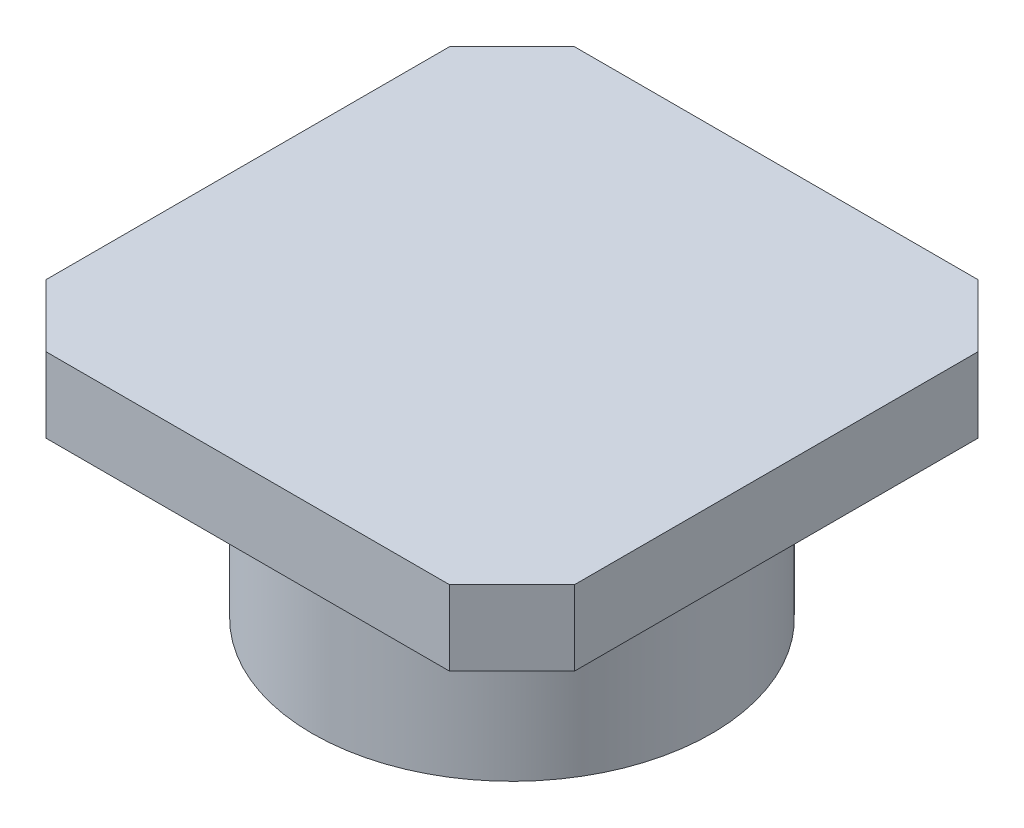
SolidWorks part; units mm, degrees
ref_plane "Front Plane" through (0, 0, 0) normal (0, 0, 1) x (1, 0, 0)
ref_plane "Top Plane" through (0, 0, 0) normal (0, 1, 0) x (1, 0, 0)
ref_plane "Right Plane" through (0, 0, 0) normal (1, 0, 0) x (0, 0, -1)
sketch "Sketch1" plane through (0, 0, 0) normal (0, 1, 0) x (1, 0, 0)
  circle A0 centre (0, 0) radius 12.5
  circle A1 centre (0, 0) radius 16
extrude "Extrude1" add sketch "Sketch1" along normal blind 15
sketch "Sketch2" plane through (0, 15, 0) normal (0, 1, 0) x (1, 0, 0)
  circle A0 centre (0, 0) radius 30
extrude "Extrude2" add sketch "Sketch2" along normal blind 6
fillet "Fillet1" radius 2 1 edges at (0, 15, 16)
sketch "Sketch5" plane through (0, 21, 0) normal (0, 1, 0) x (1, 0, 0)
  line L0 (-21.1693, 16.1693) -> (-16.1693, 21.1693)
  line L1 (-34.3735, 34.3735) -> (34.3735, 34.3735)
  line L2 (-34.3735, 34.3735) -> (-34.3735, -34.3735)
  line L3 (-34.3735, -34.3735) -> (34.3735, -34.3735)
  line L4 (34.3735, 34.3735) -> (34.3735, -34.3735)
  line L5 (-34.3735, 34.3735) -> (34.3735, -34.3735) construction
  line L6 (-34.3735, -34.3735) -> (34.3735, 34.3735) construction
  line L7 (-16.1693, -21.1693) -> (16.1693, -21.1693)
  line L8 (-21.1693, -16.1693) -> (-21.1693, 16.1693)
  line L9 (-16.1693, 21.1693) -> (16.1693, 21.1693)
  line L10 (21.1693, -16.1693) -> (21.1693, 16.1693)
  line L11 (-21.1693, -21.1693) -> (21.1693, 21.1693) construction
  line L12 (-21.1693, 21.1693) -> (21.1693, -21.1693) construction
  line L13 (16.1693, 21.1693) -> (21.1693, 16.1693)
  line L14 (16.1693, -21.1693) -> (21.1693, -16.1693)
  line L15 (-21.1693, -16.1693) -> (-16.1693, -21.1693)
  point P0 (0, 0)
  dimension "D13" = 5
  dimension "D14" = 5
  dimension "D15" = 5
  dimension "D16" = 5
extrude "Cut-Extrude2" cut sketch "Sketch5" against normal blind 10
